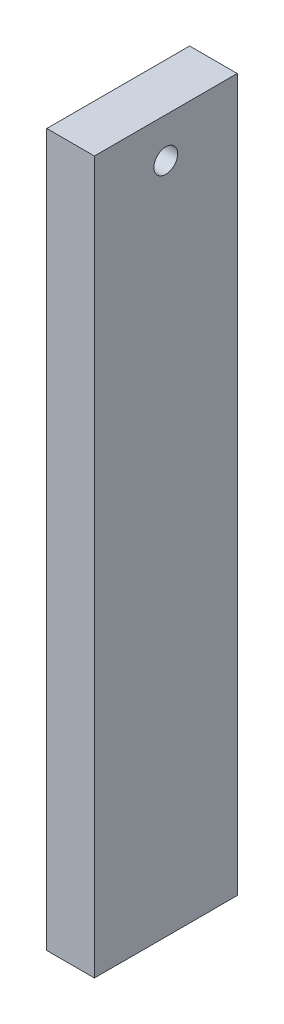
SolidWorks part; units mm, degrees
ref_plane "Front Plane" through (0, 0, 0) normal (0, 0, 1) x (1, 0, 0)
ref_plane "Top Plane" through (0, 0, 0) normal (0, 1, 0) x (1, 0, 0)
ref_plane "Right Plane" through (0, 0, 0) normal (1, 0, 0) x (0, 0, -1)
sketch "Sketch1" plane through (0, 0, 0) normal (0, 0, 1) x (1, 0, 0)
  line L1 (-0.5336, 0.8917) -> (1.4664, 0.8917)
  line L2 (-0.5336, 0.8917) -> (-0.5336, -6.0064)
  line L3 (-0.5336, -6.0064) -> (1.4664, -6.0064)
  line L4 (1.4664, 0.8917) -> (1.4664, -6.0064)
  dimension "D1" = 2
extrude "Boss-Extrude1" add sketch "Sketch1" along normal blind 4
sketch "Sketch2" plane through (0, 0.8917, 0) normal (0, 1, 0) x (1, 0, 0)
  line L1 (-0.5336, 0) -> (1.4664, 0)
  line L2 (-0.5336, 0) -> (-0.5336, -4)
  line L3 (-0.5336, -4) -> (1.4664, -4)
  line L4 (1.4664, 0) -> (1.4664, -4)
extrude "Boss-Extrude2" add sketch "Sketch2" along normal blind 23
sketch "Sketch3" plane through (1.4664, 0, 0) normal (1, 0, 0) x (0, 0, -1)
  line L0 (-4, 23.8917) -> (-5, 23.8917)
  line L1 (0, 23.8917) -> (1, 23.8917)
  line L3 (-5, 23.8917) -> (1, 23.8917)
  line L4 (-5, 23.8917) -> (-5, -6.0034)
  line L5 (-5, -6.0034) -> (1, -6.0034)
  line L6 (1, 23.8917) -> (1, -6.0034)
  line L7 (-5, 23.8917) -> (1, 23.8917)
  line L8 (-5, 23.8917) -> (-5, -6.0034)
  line L9 (-5, -6.0034) -> (1, -6.0034)
  line L10 (1, 23.8917) -> (1, -6.0034)
  circle A0 centre (-2, 22.2257) radius 0.5
  line M1 (0, -6.0064) -> (0, 23.8917)
  line M2 (0, 23.8917) -> (-4, 23.8917)
  line M3 (-4, 23.8917) -> (-4, -6.0064)
extrude "Boss-Extrude4" add sketch "Sketch3" against normal through all contours L5 A0 M3 M1 M2 | L4 L5 L0 M3 | L6 L1 L5 M1
sketch "Sketch4" plane through (1.4664, 0, 0) normal (1, 0, 0) x (0, 0, -1)
  circle A0 centre (-2, 22.2257) radius 0.5
extrude "Cut-Extrude1" cut sketch "Sketch4" against normal through all both and the other way through all
